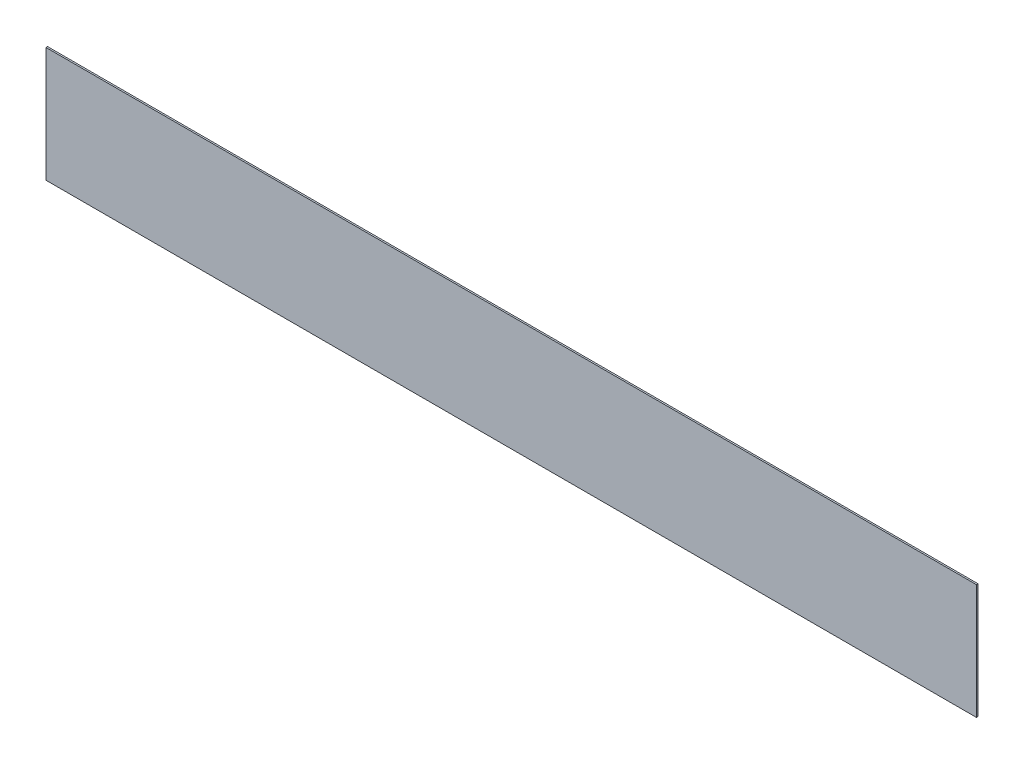
SolidWorks part; units mm, degrees
ref_plane "Front Plane" through (0, 0, 0) normal (0, 0, 1) x (1, 0, 0)
ref_plane "Top Plane" through (0, 0, 0) normal (0, 1, 0) x (1, 0, 0)
ref_plane "Right Plane" through (0, 0, 0) normal (1, 0, 0) x (0, 0, -1)
other "Configuration Table"
sketch "Sketch1" plane through (0, 0, 0) normal (0, 0, 1) x (1, 0, 0)
  line L1 (13.7, 8) -> (604.3, 8)
  line L2 (13.7, 8) -> (13.7, 81)
  line L3 (13.7, 81) -> (604.3, 81)
  line L4 (604.3, 8) -> (604.3, 81)
extrude "CEK_taze_kutu_arka_1.0_1" add sketch "Sketch1" against normal blind 1 from offset 699 separate body
